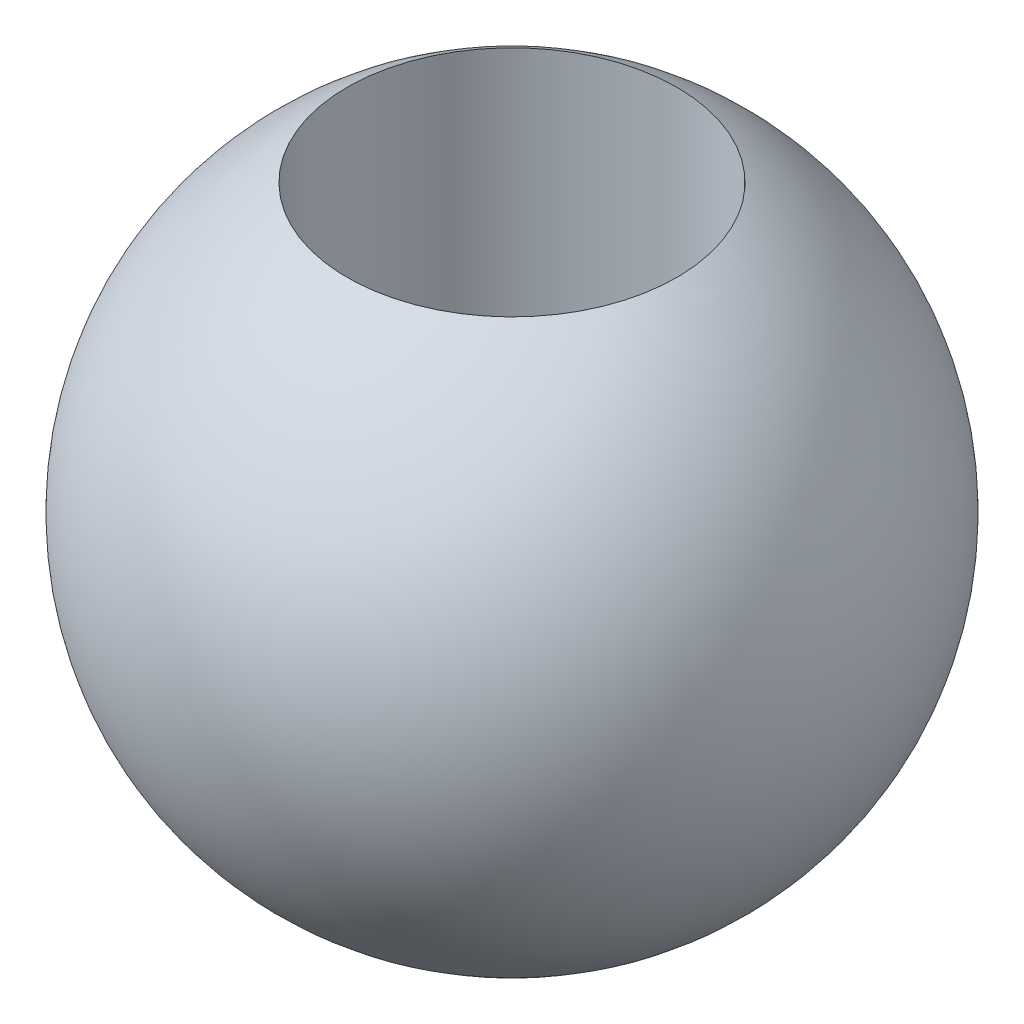
SolidWorks part; units mm, degrees
ref_plane "Front Plane" through (0, 0, 0) normal (1, 0, 0) x (0, 1, 0)
ref_plane "Top Plane" through (0, 0, 0) normal (0, 0, 1) x (0, 1, 0)
ref_plane "Right Plane" through (0, 0, 0) normal (0, 1, 0) x (-1, 0, 0)
sketch "Sketch1" plane through (0, 0, 0) normal (0, 1, 0) x (-1, 0, 0)
  line L0 (-8, 0) -> (8, 0)
  arc A0 (8, 0) -> (-8, 0) centre (0, 0) ccw
  dimension "D1" = 8
revolve "Revolve1" add sketch "Sketch1" angle 360 about L0
sketch "Sketch2" plane through (0, 0, 0) normal (0, 1, 0) x (-1, 0, 0)
  circle A0 centre (0, 0) radius 4
  dimension "D1" = 8
extrude "Cut-Extrude1" cut sketch "Sketch2" against normal up to surface and the other way up to surface
